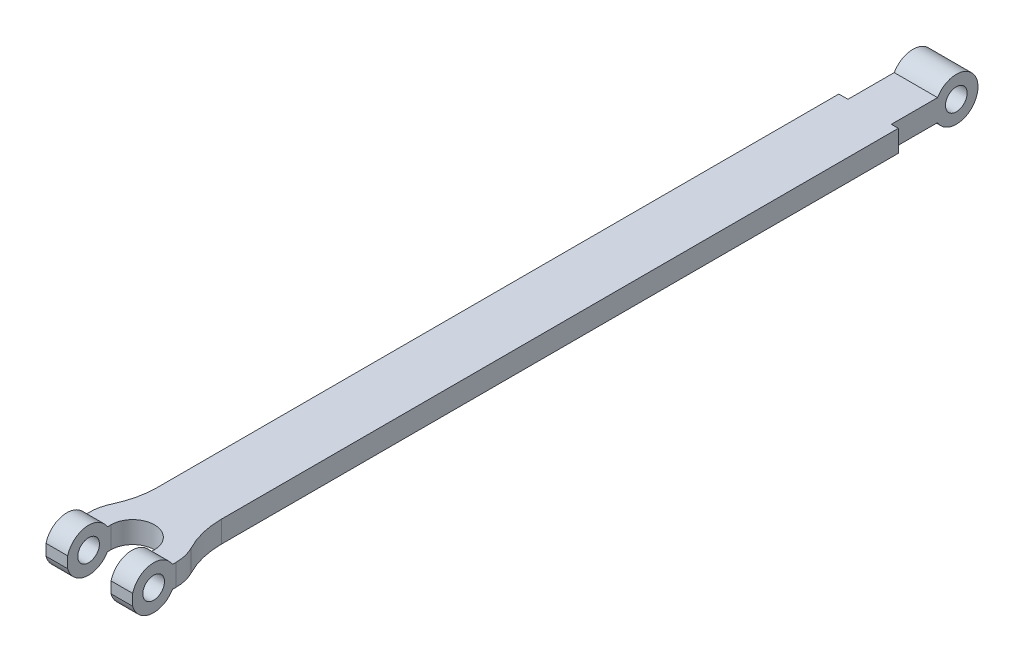
SolidWorks part; units mm, degrees
ref_plane "Front Plane" through (0, 0, 0) normal (0, 0, 1) x (1, 0, 0)
ref_plane "Top Plane" through (0, 0, 0) normal (0, 1, 0) x (1, 0, 0)
ref_plane "Right Plane" through (0, 0, 0) normal (1, 0, 0) x (0, 0, -1)
sketch "Sketch3" plane through (0, 0, 0) normal (0, 1, 0) x (1, 0, 0)
  line L0 (0, 60) -> (0, -61.513) construction
  line L1 (10, -59.8354) -> (-10, -59.8354)
  line L2 (10, -59.8354) -> (10, 140.1646)
  line L3 (10, 140.1646) -> (-10, 140.1646)
  line L4 (-10, -59.8354) -> (-10, 140.1646)
  line L5 (-7.1057, -36.9793) -> (-7.1057, 120.1646)
  line L6 (6.6091, -35.9805) -> (6.6091, 120.1646)
  line L7 (-5, 120.1646) -> (-5, 140.1646)
  line L8 (-5, -49.8354) -> (-5, -59.8354)
  line L9 (-7.1057, 120.1646) -> (-5, 120.1646)
  line L12 (5, 120.1646) -> (5, 140.1646)
  line L13 (5, -49.8354) -> (5, -59.8354)
  line L14 (5, 120.1646) -> (6.6091, 120.1646)
  arc A0 (-9.0352, -45.55) -> (8.8697, -45.2171) centre (0, -49.8354) ccw
  circle A1 centre (0, -49.8354) radius 5
  arc A2 (8.8697, -45.2171) -> (6.6091, -35.9805) centre (26.6091, -35.9805) cw
  arc A3 (-9.0352, -45.55) -> (-7.1057, -36.9793) centre (-27.1057, -36.9793) ccw
  point P0 (0, 0)
  point P24 (0, 0)
  dimension "D3" = 10
  dimension "D6" = 20
  dimension "D4" = 10
  dimension "D1" = 20
  dimension "D2" = 200
  dimension "D5" = 20
extrude "Boss-Extrude2" add sketch "Sketch3" along normal blind 10 contours L3 L0 A1 L13 A0 A2 L6 L14 L12 | L0 L3 L7 L9 L5 A3 A0 L8 A1 | A0 L4 L1 L8 | A0 L13 L1 L2
sketch "Sketch7" plane through (-10, 0, 0) normal (-1, 0, 0) x (0, 0, 1)
  line L0 (59.8354, 0) -> (49.8354, 0) construction
  line L1 (36.9793, 10) -> (-120.1646, 10) construction
  line L2 (-130.8345, 7.5) -> (50.6754, 7.5)
  line L4 (-130.8345, 2.5) -> (50.6754, 2.5)
  line L8 (45.55, 0) -> (49.8354, 0) construction
  line L9 (49.8354, 10) -> (45.55, 10) construction
  line L10 (45.55, 10) -> (36.9793, 10) construction
  line L11 (36.9793, 0) -> (45.55, 0) construction
  line L12 (36.9793, 0) -> (-120.1646, 0) construction
  line L13 (-120.1646, 0) -> (-140.1646, 0) construction
  line L14 (-140.1646, 10) -> (-140.1646, 0) construction
  line L15 (-120.1646, 10) -> (-140.1646, 10) construction
  line L16 (45.55, 0) -> (49.8354, 0)
  line L17 (49.8354, 10) -> (45.55, 10)
  line L18 (45.55, 10) -> (36.9793, 10)
  line L19 (36.9793, 0) -> (45.55, 0)
  line L20 (36.9793, 10) -> (-120.1646, 10)
  line L21 (36.9793, 0) -> (-120.1646, 0)
  line L22 (-120.1646, 0) -> (-140.1646, 0)
  line L23 (-140.1646, 10) -> (-140.1646, 0)
  line L24 (-120.1646, 10) -> (-140.1646, 10)
  line L27 (-140.1646, 0) -> (-120.1646, 0)
  line L28 (-120.1646, 0) -> (-120.1646, 10)
  line L29 (-120.1646, 10) -> (-140.1646, 10)
  line L30 (-140.1646, 10) -> (-140.1646, 0)
  line L31 (-140.1646, 0) -> (-120.1646, 0)
  line L32 (-120.1646, 0) -> (-120.1646, 10)
  line L33 (-120.1646, 10) -> (-140.1646, 10)
  line L34 (-140.1646, 10) -> (-140.1646, 0)
  arc A0 (50.6754, 2.5) -> (50.6754, 7.5) centre (55.0055, 5) ccw
  circle A1 centre (55.0055, 5) radius 2.5
  arc A2 (-130.8345, 7.5) -> (-130.8345, 2.5) centre (-135.1646, 5) ccw
  circle A3 centre (-135.1646, 5) radius 2.5
  point P8 (-140.1646, 5)
  line M8 (49.8354, 0) -> (59.8354, 0)
  line M9 (59.8354, 0) -> (59.8354, 10)
  line M10 (59.8354, 10) -> (49.8354, 10)
  line M11 (49.8354, 10) -> (49.8354, 0)
  dimension "D2" = 10
  dimension "D3" = 5
  dimension "D4" = 5
  dimension "D6" = 10
  dimension "D1" = 5
  dimension "D5" = 2.5
  dimension "D7" = 5
  dimension "D8" = 0
extrude "Cut-Extrude1" cut sketch "Sketch7" against normal through all contours A2 L33 L23 | A2 L34 L31 | A2 L2 L32 L24 | A2 L22 L32 L4 | L32 L21 L19 L16 L4 M11 | L32 L2 L17 L18 L20 M11 | A0 L2 M10 M11 | A0 M9 M10 | A0 M8 M9 | A0 L4 M11 M8 | A1 | A3
